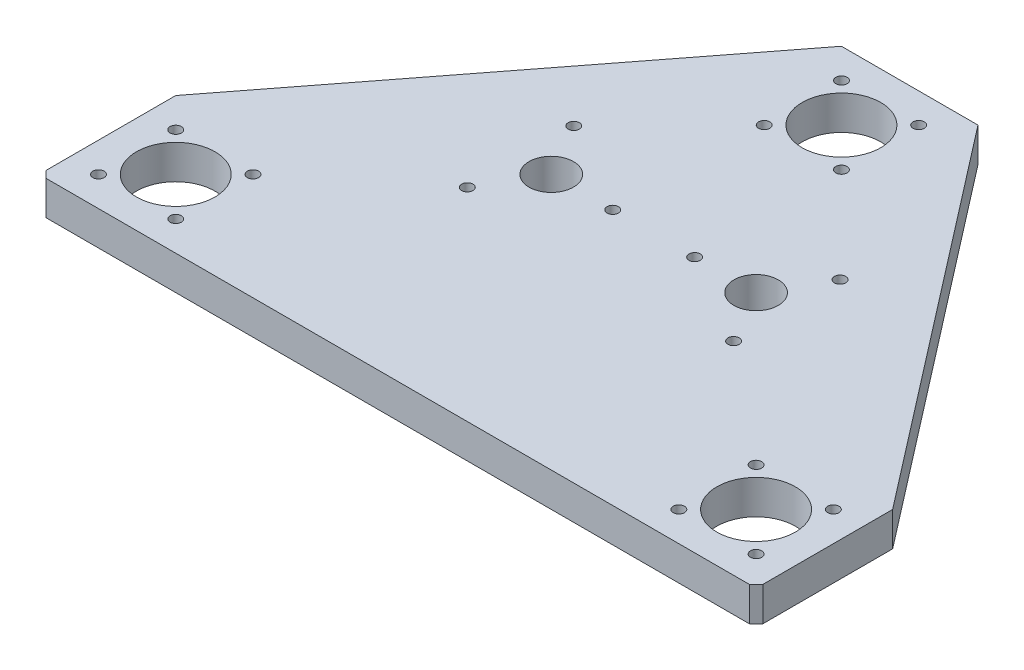
SolidWorks part; units mm, degrees
ref_plane "Front Plane" through (0, 0, 0) normal (0, 0, 1) x (1, 0, 0)
ref_plane "Top Plane" through (0, 0, 0) normal (0, 1, 0) x (1, 0, 0)
ref_plane "Right Plane" through (0, 0, 0) normal (1, 0, 0) x (0, 0, -1)
sketch "Sketch1" plane through (0, 0, 0) normal (0, 1, 0) x (1, 0, 0)
  line L0 (0, 0) -> (0, 55) construction
  line L1 (0, 0) -> (-85, -55) construction
  line L2 (0, 0) -> (85, -55) construction
  line L3 (0, 0) -> (-30, 0) construction
  line L4 (0, 0) -> (30, 0) construction
  line L5 (-105, -35) -> (-20, 75)
  line L6 (-65, -75) -> (-105, -75)
  line L7 (-65, -75) -> (-65, -35) construction
  line L8 (-65, -35) -> (-105, -35) construction
  line L9 (-105, -75) -> (-105, -35)
  line L10 (-65, -75) -> (-105, -35) construction
  line L11 (-65, -35) -> (-105, -75) construction
  line L12 (105, -75) -> (65, -75)
  line L13 (105, -75) -> (105, -35)
  line L14 (105, -35) -> (65, -35) construction
  line L15 (65, -75) -> (65, -35) construction
  line L16 (105, -75) -> (65, -35) construction
  line L17 (105, -35) -> (65, -75) construction
  line L18 (20, 35) -> (-20, 35) construction
  line L19 (20, 35) -> (20, 75) construction
  line L20 (20, 75) -> (-20, 75)
  line L21 (-20, 35) -> (-20, 75) construction
  line L22 (20, 35) -> (-20, 75) construction
  line L23 (20, 75) -> (-20, 35) construction
  line L24 (20, 75) -> (105, -35)
  line L25 (-65, -75) -> (65, -75)
  circle A0 centre (-30, 0) radius 6.5
  circle A1 centre (30, 0) radius 6.5
  circle A2 centre (0, 55) radius 11.5
  circle A3 centre (85, -55) radius 11.5
  circle A4 centre (-85, -55) radius 11.5
  circle A5 centre (-30, 0) radius 20 construction
  circle A6 centre (30, 0) radius 20 construction
  dimension "D5" = 13
  dimension "D6" = 23
  dimension "D8" = 40
  dimension "D1" = 55
  dimension "D2" = 55
  dimension "D3" = 85
  dimension "D4" = 60
  dimension "D7" = 40
extrude "Boss-Extrude1" add sketch "Sketch1" along normal blind 10
chamfer "Chamfer1" distance 2 angle 45 2 edges at (105, 5, 75) (-105, 5, 75)
sketch "Sketch2" plane through (0, 10, 0) normal (0, 1, 0) x (1, 0, 0)
  line L0 (-30, 0) -> (-12, 0) construction
  line L2 (11.3137, 43.6863) -> (-11.3137, 43.6863)
  line L3 (11.3137, 43.6863) -> (11.3137, 66.3137)
  line L4 (11.3137, 66.3137) -> (-11.3137, 66.3137)
  line L5 (-11.3137, 43.6863) -> (-11.3137, 66.3137)
  line L6 (11.3137, 43.6863) -> (-11.3137, 66.3137) construction
  line L7 (11.3137, 66.3137) -> (-11.3137, 43.6863) construction
  line L8 (-73.6863, -66.3137) -> (-96.3137, -66.3137)
  line L9 (-73.6863, -66.3137) -> (-73.6863, -43.6863)
  line L10 (-73.6863, -43.6863) -> (-96.3137, -43.6863)
  line L11 (-96.3137, -66.3137) -> (-96.3137, -43.6863)
  line L12 (-73.6863, -66.3137) -> (-96.3137, -43.6863) construction
  line L13 (-73.6863, -43.6863) -> (-96.3137, -66.3137) construction
  point P2 (0, 55)
  point P3 (-12, 0)
  point P11 (-85, -55)
  dimension "D1" = 32
  dimension "D2" = 32
  dimension "D3" = 18
hole_wizard "M4x0.7 Tapped Hole1" positions "3DSketch1" profile "Sketch3" tap size "M4x0.7" standard "BSI" end condition through all
sketch3d "3DSketch1"
  point P0 (-96.3137, 10, 43.6863)
  point P3 (-73.6863, 10, 43.6863)
  point P6 (-73.6863, 10, 66.3137)
  point P9 (-96.3137, 10, 66.3137)
  point P15 (-11.3137, 10, -43.6863)
  point P18 (-11.3137, 10, -66.3137)
sketch "Sketch3" plane through (-96.3137, 10, 43.6863) normal (1, 0, 0) x (0, 0, 1)
  line L0 (0, 0) -> (0, 10)
  line L1 (0, 10) -> (1.65, 10)
  line L2 (1.65, 10) -> (1.65, 0)
  line L5 (1.65, 0) -> (0, 0)
  line L11 (0, -6.35) -> (0, 107.95) construction
  dimension "Thru Tap Drill Dia." = 3.3
  dimension "Thru Tap Drill Depth" = 10
cosmetic thread "Hole Thread1" parameters "D2"=4
cosmetic thread "Hole Thread2" parameters "D2"=4
cosmetic thread "Hole Thread4" parameters "D2"=4
cosmetic thread "Hole Thread5" parameters "D2"=4
cosmetic thread "Hole Thread6" parameters "D2"=4
cosmetic thread "Hole Thread7" parameters "D2"=4
hole_wizard "M4x0.7 Tapped Hole2" positions "3DSketch2" profile "Sketch4" tap size "M4x0.7" standard "BSI" end condition through all
sketch3d "3DSketch2"
  point P0 (-12, 10, 0)
sketch "Sketch4" plane through (-12, 10, 0) normal (1, 0, 0) x (0, 0, 1)
  line L0 (0, 0) -> (0, 10)
  line L1 (0, 10) -> (1.65, 10)
  line L2 (1.65, 10) -> (1.65, 0)
  line L5 (1.65, 0) -> (0, 0)
  line L11 (0, -6.35) -> (0, 107.95) construction
  dimension "Thru Tap Drill Dia." = 3.3
  dimension "Thru Tap Drill Depth" = 10
cosmetic thread "Hole Thread8" parameters "D2"=4
pattern_circular "CirPattern1" count 3 over 360 about axis through (-30, 0, 0) along (0, 1, 0) of "M4x0.7 Tapped Hole2"
cosmetic thread "Hole Thread9" parameters "D2"=4
cosmetic thread "Hole Thread10" parameters "D2"=4
mirror "Mirror1" about plane through (0, 0, 0) normal (1, 0, 0) of "CirPattern1", "M4x0.7 Tapped Hole2", "M4x0.7 Tapped Hole1"
cosmetic thread "Hole Thread11" parameters "D2"=4
cosmetic thread "Hole Thread12" parameters "D2"=4
cosmetic thread "Hole Thread13" parameters "D2"=4
cosmetic thread "Hole Thread14" parameters "D2"=4
cosmetic thread "Hole Thread15" parameters "D2"=4
cosmetic thread "Hole Thread16" parameters "D2"=4
cosmetic thread "Hole Thread17" parameters "D2"=4
cosmetic thread "Hole Thread18" parameters "D2"=4
cosmetic thread "Hole Thread19" parameters "D2"=4
